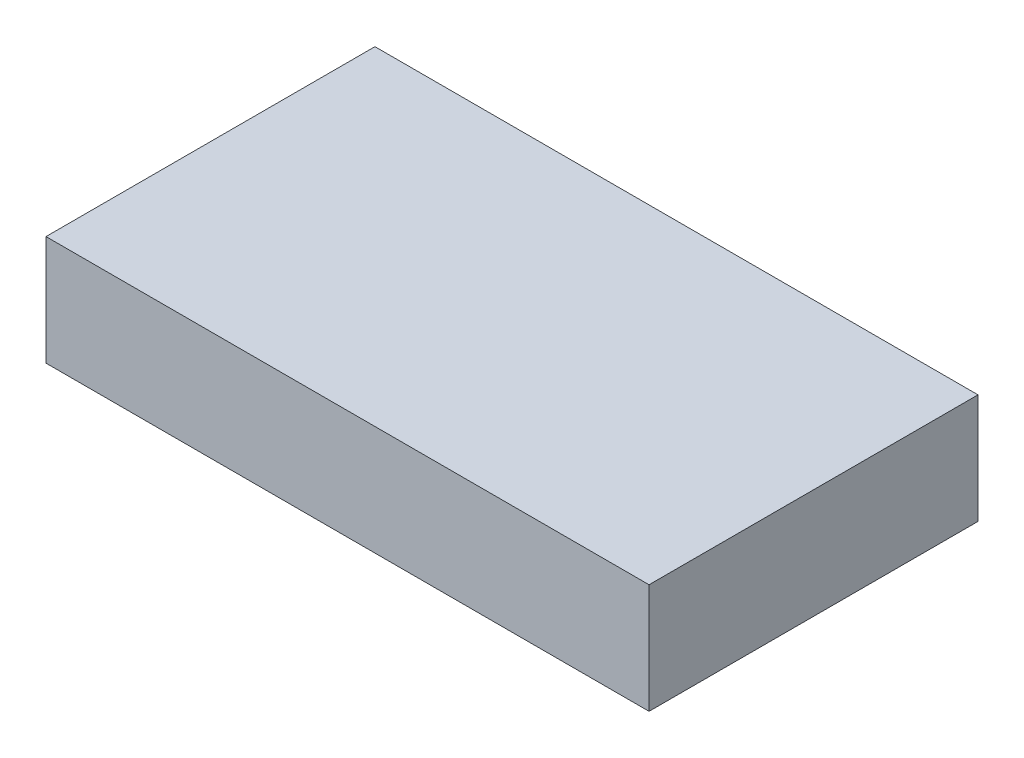
SolidWorks part; units mm, degrees
ref_plane "Front Plane" through (0, 0, 0) normal (0, 0, 1) x (1, 0, 0)
ref_plane "Top Plane" through (0, 0, 0) normal (0, 1, 0) x (1, 0, 0)
ref_plane "Right Plane" through (0, 0, 0) normal (1, 0, 0) x (0, 0, -1)
sketch "Sketch1" plane through (0, 0, 0) normal (0, 1, 0) x (1, 0, 0)
  line L1 (0, 0) -> (-55.88, 0)
  line L2 (0, 0) -> (0, 30.48)
  line L3 (0, 30.48) -> (-55.88, 30.48)
  line L4 (-55.88, 0) -> (-55.88, 30.48)
  dimension "D1" = 30.48
  dimension "D2" = 55.88
extrude "Boss-Extrude1" add sketch "Sketch1" along normal blind 10.16
